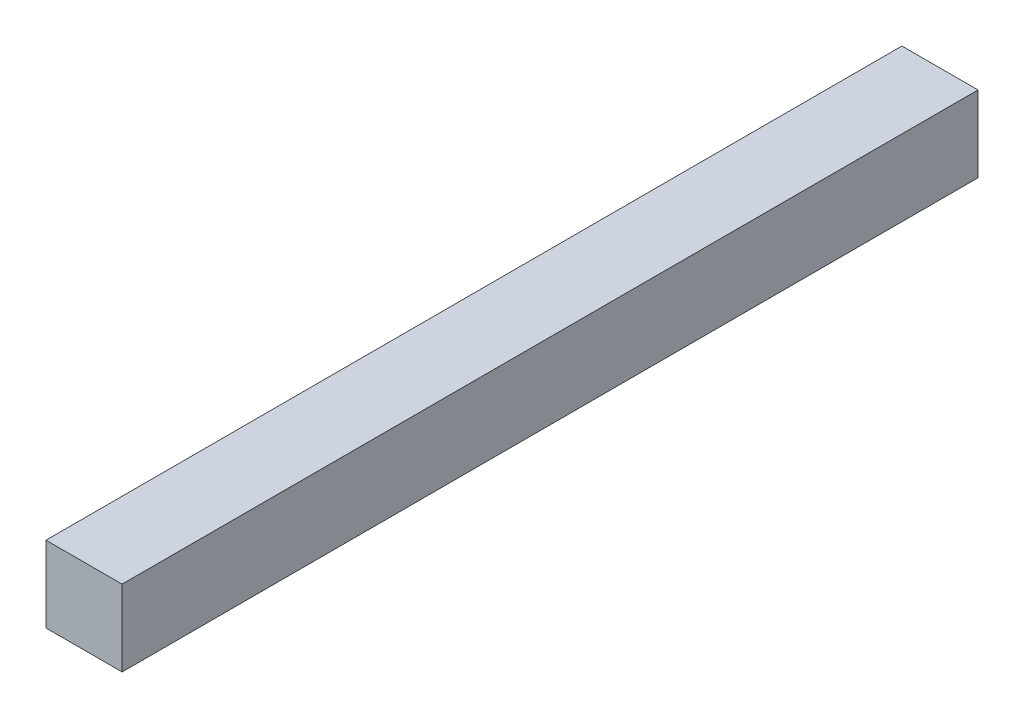
SolidWorks part; units mm, degrees
ref_plane "Alzado" through (0, 0, 0) normal (0, 0, 1) x (1, 0, 0)
ref_plane "Planta" through (0, 0, 0) normal (0, 1, 0) x (1, 0, 0)
ref_plane "Vista lateral" through (0, 0, 0) normal (1, 0, 0) x (0, 0, -1)
sketch "Croquis1" plane through (0, 0, 0) normal (0, 0, 1) x (1, 0, 0)
  line L1 (0, 0) -> (88.9, 0)
  line L2 (0, 0) -> (0, -88.9)
  line L3 (0, -88.9) -> (88.9, -88.9)
  line L4 (88.9, 0) -> (88.9, -88.9)
  dimension "D1" = 88.9
  dimension "D2" = 88.9
extrude "Saliente-Extruir1" add sketch "Croquis1" along normal blind 1000
